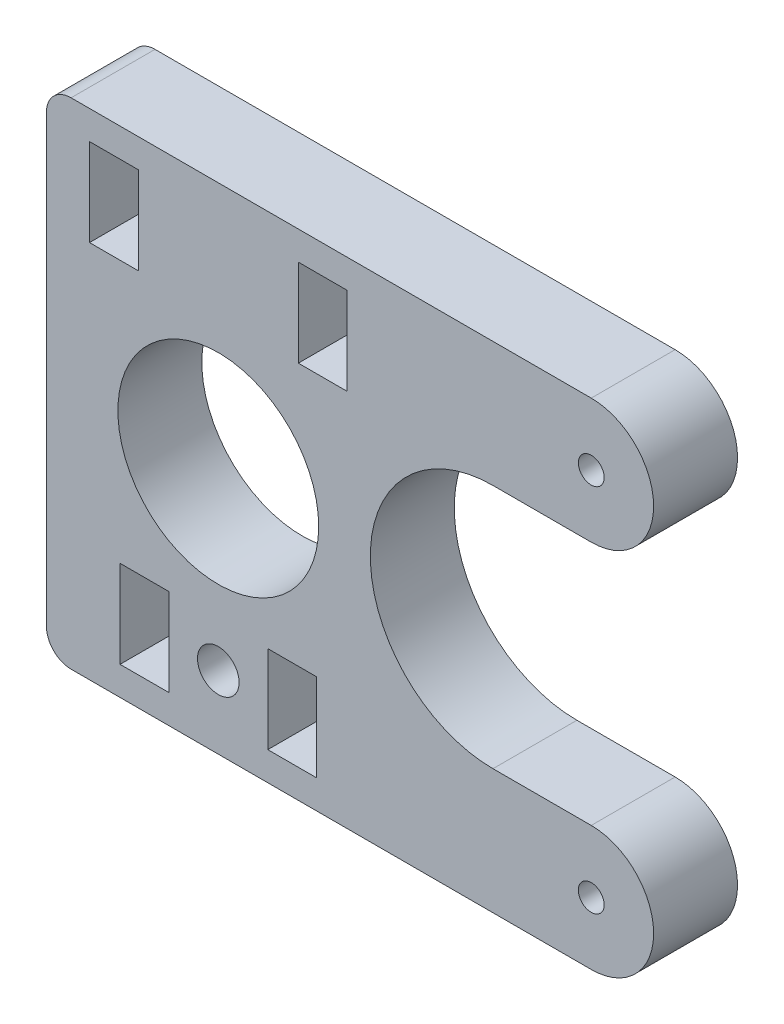
SolidWorks part; units mm, degrees
material "Acrylic (Medium-high impact)"
ref_plane "Front Plane" through (0, 0, 0) normal (0, 0, 1) x (1, 0, 0)
ref_plane "Top Plane" through (0, 0, 0) normal (0, 1, 0) x (1, 0, 0)
ref_plane "Right Plane" through (0, 0, 0) normal (1, 0, 0) x (0, 0, -1)
sketch "Sketch1" plane through (0, 0, 0) normal (0, 0, 1) x (1, 0, 0)
  line L0 (669.2168, 348.0155) -> (648.4638, 348.0155)
  line L1 (646.7465, 346.2982) -> (646.7465, 315.2328)
  line L2 (648.4638, 313.5155) -> (669.2168, 313.5155)
  line L3 (653.1465, 339.9155) -> (653.1465, 346.0155)
  line L4 (653.1465, 346.0155) -> (649.7465, 346.0155)
  line L5 (649.7465, 346.0155) -> (649.7465, 339.9155)
  line L6 (649.7465, 339.9155) -> (653.1465, 339.9155)
  line L7 (651.8765, 315.5155) -> (655.2765, 315.5155)
  line L8 (655.2765, 315.5155) -> (655.2765, 321.6155)
  line L9 (655.2765, 321.6155) -> (651.8765, 321.6155)
  line L10 (651.8765, 321.6155) -> (651.8765, 315.5155)
  line L11 (667.7065, 339.9155) -> (667.7065, 346.0155)
  line L12 (667.7065, 346.0155) -> (664.3065, 346.0155)
  line L13 (664.3065, 346.0155) -> (664.3065, 339.9155)
  line L14 (664.3065, 339.9155) -> (667.7065, 339.9155)
  line L15 (662.1765, 321.6155) -> (662.1765, 315.5155)
  line L16 (662.1765, 315.5155) -> (665.5765, 315.5155)
  line L17 (665.5765, 315.5155) -> (665.5765, 321.6155)
  line L18 (665.5765, 321.6155) -> (662.1765, 321.6155)
  line L19 (-318.4867, 330.7655) -> (49681.5133, 330.7655) construction
  line L21 (653.1465, 339.9155) -> (664.3065, 339.9155) construction
  line L22 (657.2765, 318.5655) -> (655.2765, 318.5655) construction
  line L23 (660.1765, 318.5655) -> (662.1765, 318.5655) construction
  line L24 (658.7265, -664.2806) -> (658.7265, 49335.7194) construction
  line L25 (669.2168, 313.5155) -> (684.7265, 313.5155)
  line L26 (669.2168, 348.0155) -> (684.7265, 348.0155)
  line L27 (684.7265, 317.8655) -> (684.7265, 330.7655) construction
  line L28 (684.7265, 330.7655) -> (684.7265, 343.6655) construction
  line L29 (684.7265, -668.8222) -> (684.7265, 49331.1778) construction
  line L30 (662.1765, 330.7655) -> (662.1765, 348.0155) construction
  line L31 (662.1765, 330.7655) -> (662.1765, 313.5155) construction
  line L32 (684.7265, 339.3155) -> (677.8765, 339.3155)
  line L33 (684.7265, 322.2155) -> (677.8765, 322.2155)
  circle A0 centre (684.7265, 343.6655) radius 0.9
  circle A1 centre (684.7265, 317.8655) radius 0.9
  arc A2 (684.7265, 313.5155) -> (684.7265, 322.2155) centre (684.7265, 317.8655) ccw
  circle A3 centre (658.7265, 318.5655) radius 1.45
  arc A4 (648.4638, 348.0155) -> (646.7465, 346.2982) centre (648.4638, 346.2982) ccw
  arc A5 (684.7265, 348.0155) -> (684.7265, 339.3155) centre (684.7265, 343.6655) cw
  arc A6 (677.8765, 339.3155) -> (677.8765, 322.2155) centre (677.8765, 330.7655) ccw
  arc A7 (646.7465, 315.2328) -> (648.4638, 313.5155) centre (648.4638, 315.2328) ccw
  circle A8 centre (658.7265, 330.7655) radius 7
  point P27 (658.7265, 339.9155)
  point P38 (669.3265, 330.7655)
  point P39 (665.7265, 330.7655)
  dimension "D5" = 2.9
  dimension "D12" = 3.6
  dimension "D13" = 14
  dimension "D14" = 1.8
  dimension "D15" = 1.7173
  dimension "D10" = 26
  dimension "D1" = 2
  dimension "D2" = 6.1
  dimension "D3" = 3.4
  dimension "D4" = 3.4
  dimension "D6" = 11.16
  dimension "D7" = 2
  dimension "D8" = 3
  dimension "D9" = 2
  dimension "D11" = 12.9
  dimension "D16" = 34.5
  dimension "D17" = 18.3
extrude "Boss-Extrude2" add sketch "Sketch1" along normal blind 5.85
